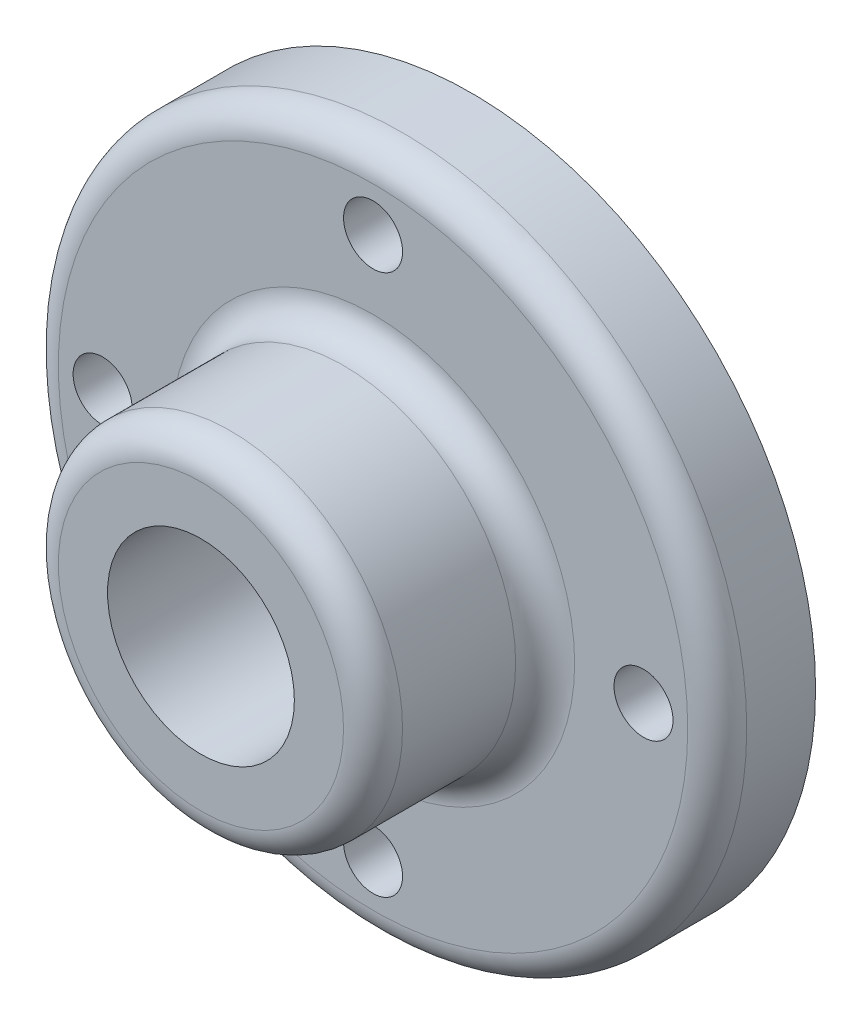
SolidWorks part; units mm, degrees
ref_plane "Front Plane" through (0, 0, 0) normal (0, 0, 1) x (1, 0, 0)
ref_plane "Top Plane" through (0, 0, 0) normal (0, 1, 0) x (1, 0, 0)
ref_plane "Right Plane" through (0, 0, 0) normal (1, 0, 0) x (0, 0, -1)
sketch "Sketch1" plane through (0, 0, 0) normal (0, 1, 0) x (1, 0, 0)
  line L0 (0, 0) -> (0, 85.9507) construction
  line L1 (19, 0) -> (19, 55)
  line L2 (19, 55) -> (70, 55)
  line L3 (70, 55) -> (70, 41)
  line L4 (64, 35) -> (41, 35)
  line L5 (35, 29) -> (35, 6)
  line L6 (29, 0) -> (19, 0)
  arc A0 (41, 35) -> (35, 29) centre (41, 29) ccw
  arc A1 (70, 41) -> (64, 35) centre (64, 41) cw
  arc A2 (35, 6) -> (29, 0) centre (29, 6) cw
  dimension "D6" = 6
  dimension "D1" = 140
  dimension "D2" = 70
  dimension "D3" = 55
  dimension "D4" = 20
  dimension "D5" = 38
revolve "Revolve1" add sketch "Sketch1" angle 360 about L0
hole_wizard "Ø12.0 (12) Diameter Hole1" positions "Sketch3" profile "Sketch2" hole size "Ø12.0" standard "ANSI Metric" end condition through all
sketch "Sketch3" plane through (0, 0, -35) normal (0, 0, 1) x (1, 0, 0)
  circle A0 centre (0, 0) radius 55 construction
  point P0 (0, 55)
  point P2 (55, 0)
  point P4 (0, -55)
  point P6 (-55, 0)
  dimension "D1" = 110
sketch "Sketch2" plane through (0, 55, -35) normal (1, 0, 0) x (0, -1, 0)
  line L0 (0, 0) -> (0, 20)
  line L1 (0, 20) -> (6, 20)
  line L2 (6, 20) -> (6, 0)
  line L5 (6, 0) -> (0, 0)
  line L11 (0, -6.35) -> (0, 107.95) construction
  dimension "Thru Hole Dia." = 12
  dimension "Thru Hole Depth" = 20
